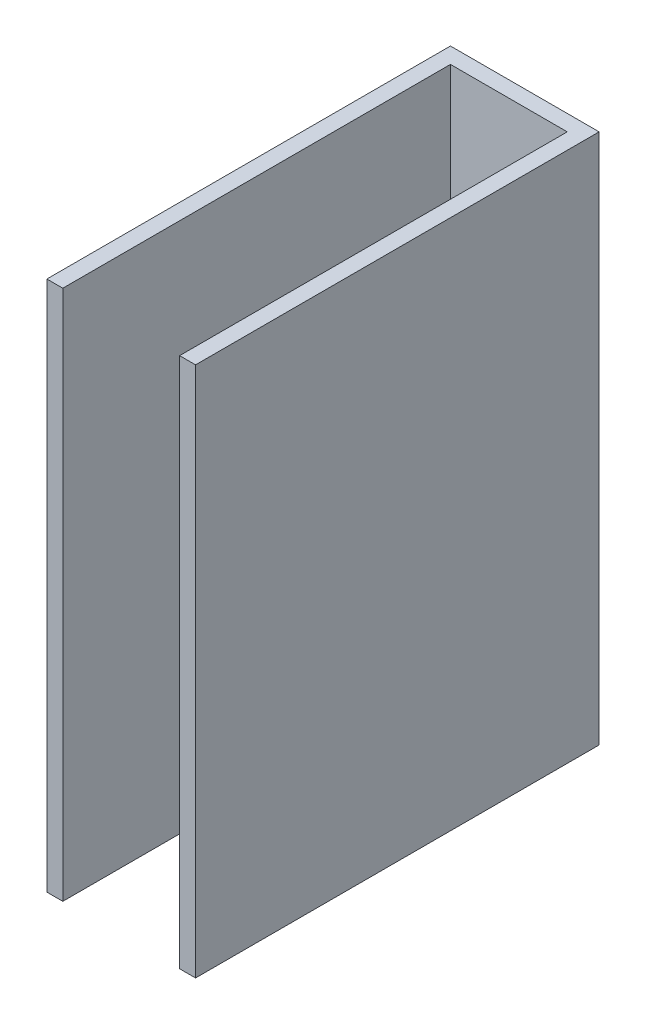
SolidWorks part; units mm, degrees
ref_plane "Front" through (0, 0, 0) normal (0, 0, 1) x (1, 0, 0)
ref_plane "Top" through (0, 0, 0) normal (0, 1, 0) x (1, 0, 0)
ref_plane "Right" through (0, 0, 0) normal (1, 0, 0) x (0, 0, -1)
sketch "Sketch1" plane through (0, 0, 0) normal (0, 1, 0) x (1, 0, 0)
  line L0 (0, 0) -> (0, -73)
  line L1 (0, 0) -> (22, 0)
  line L2 (22, 0) -> (22, -73)
  line L3 (0, -73) -> (-3, -73)
  line L4 (-3, -73) -> (-3, 3)
  line L5 (-3, 3) -> (25, 3)
  line L6 (25, 3) -> (25, -73)
  line L7 (25, -73) -> (22, -73)
  dimension "D1" = 3
  dimension "D2" = 3
  dimension "D3" = 3
  dimension "D4" = 73
  dimension "D5" = 73
  dimension "D6" = 22
extrude "Boss-Extrude1" add sketch "Sketch1" along normal blind 100
